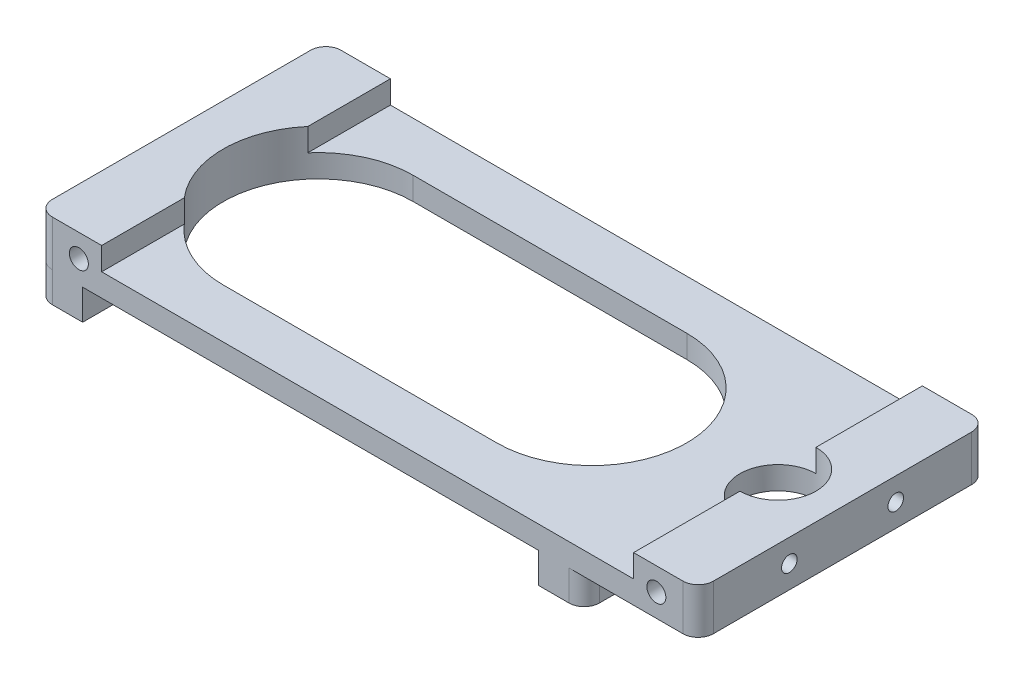
SolidWorks part; units mm, degrees
ref_plane "Front Plane" through (0, 0, 0) normal (0, 0, 1) x (1, 0, 0)
ref_plane "Top Plane" through (0, 0, 0) normal (0, 1, 0) x (1, 0, 0)
ref_plane "Right Plane" through (0, 0, 0) normal (1, 0, 0) x (0, 0, -1)
sketch "Sketch2" plane through (0, 0, 11.2) normal (0, 0, 1) x (1, 0, 0)
  line L1 (-84.0653, 85.9519) -> (-75.5653, 85.9519)
  line L2 (-84.0653, 85.9519) -> (-84.0653, 79.9519)
  line L3 (-84.0653, 79.9519) -> (2.9347, 79.9519)
  line L4 (2.9347, 85.9519) -> (2.9347, 79.9519)
  line L5 (-71.5653, 86.4519) -> (-82.0653, 86.4519) construction
  line L14 (-5.5653, 85.9519) -> (2.9347, 85.9519)
  line L16 (-75.5653, 85.9519) -> (-75.5653, 82.9519)
  line L17 (-75.5653, 82.9519) -> (-5.5653, 82.9519)
  line L18 (-5.5653, 85.9519) -> (-5.5653, 82.9519)
  circle A0 centre (-2.5653, 82.9519) radius 3 construction
  dimension "D1" = 0.5
  dimension "D2" = 5.5
  dimension "D3" = 5.5
  dimension "D4" = 6
  dimension "D5" = 3
  dimension "D6" = 8.5
extrude "Boss-Extrude1" add sketch "Sketch2" along normal blind 38
fillet "Fillet3" radius 2 4 edges at (-84.0653, 82.9519, 49.2) (-84.0653, 82.9519, 11.2) (2.9347, 82.9519, 11.2) (2.9347, 82.9519, 49.2)
sketch "Sketch3" plane through (0, 82.9519, 0) normal (0, 1, 0) x (1, 0, 0)
  line L0 (-84.0653, -47.2) -> (-84.0653, -13.2) construction
  line L1 (-5.5653, -11.2) -> (-75.5653, -11.2) construction
  line L2 (-66.0653, -42.7) -> (-30.0653, -42.7)
  line L3 (-66.0653, -17.7) -> (-30.0653, -17.7)
  arc A0 (-30.0653, -42.7) -> (-30.0653, -17.7) centre (-30.0653, -30.2) ccw
  arc A1 (-66.0653, -17.7) -> (-66.0653, -42.7) centre (-66.0653, -30.2) ccw
  dimension "D1" = 25
  dimension "D2" = 18
  dimension "D3" = 36
  dimension "D4" = 19
extrude "Cut-Extrude1" cut sketch "Sketch3" against normal through all and the other way through all
hole_wizard "M3x0.5 Tapped Hole3" positions "Sketch7" profile "Sketch6" tap size "M3x0.5" standard "Ansi Metric"
sketch "Sketch7" plane through (0, 0, 49.2) normal (0, 0, 1) x (1, 0, 0)
  line L0 (-75.5653, 82.9519) -> (-75.5653, 85.9519) construction
  line L1 (-82.0653, 79.9519) -> (0.9347, 79.9519) construction
  line L2 (-5.5653, 85.9519) -> (-5.5653, 82.9519) construction
  point P0 (-78.5653, 82.9519)
  point P1 (-2.5653, 82.9519)
  dimension "D1" = 3
  dimension "D2" = 3
  dimension "D3" = 3
  dimension "D4" = 3
sketch "Sketch6" plane through (-78.5653, 82.9519, 49.2) normal (1, 0, 0) x (0, -1, 0)
  line L0 (0, 0) -> (0, 8.2511)
  line L1 (0, 8.2511) -> (1.25, 7.5)
  line L2 (1.25, 7.5) -> (1.25, 0)
  line L5 (1.25, 0) -> (0, 0)
  line L10 (0, 8.2511) -> (-1.25, 7.5) construction
  line L11 (0, -6.35) -> (0, 107.95) construction
  dimension "Tap Drill Dia." = 2.5
  dimension "Tap Drill Depth" = 7.5
  dimension "Drill Angle" = 118
cosmetic thread "Hole Thread6" parameters "D1"=6, "D2"=3
cosmetic thread "Hole Thread7" parameters "D1"=6, "D2"=3
hole_wizard "M3x0.5 Tapped Hole4" positions "Sketch9" profile "Sketch8" tap size "M3x0.5" standard "Ansi Metric"
sketch "Sketch9" plane through (0, 0, 11.2) normal (0, 0, -1) x (-1, 0, 0)
  line L0 (75.5653, 82.9519) -> (75.5653, 85.9519) construction
  line L1 (82.0653, 79.9519) -> (-0.9347, 79.9519) construction
  line L2 (-0.9347, 85.9519) -> (5.5653, 85.9519) construction
  line L3 (5.5653, 85.9519) -> (5.5653, 82.9519) construction
  point P0 (2.5653, 82.9519)
  point P1 (78.5653, 82.9519)
  dimension "D1" = 3
  dimension "D2" = 3
  dimension "D3" = 3
  dimension "D4" = 3
sketch "Sketch8" plane through (-2.5653, 82.9519, 11.2) normal (1, 0, 0) x (0, 1, 0)
  line L0 (0, 0) -> (0, 8.2511)
  line L1 (0, 8.2511) -> (1.25, 7.5)
  line L2 (1.25, 7.5) -> (1.25, 0)
  line L5 (1.25, 0) -> (0, 0)
  line L10 (0, 8.2511) -> (-1.25, 7.5) construction
  line L11 (0, -6.35) -> (0, 107.95) construction
  dimension "Tap Drill Dia." = 2.5
  dimension "Tap Drill Depth" = 7.5
  dimension "Drill Angle" = 118
cosmetic thread "Hole Thread8" parameters "D1"=6, "D2"=3
cosmetic thread "Hole Thread9" parameters "D1"=6, "D2"=3
hole_wizard "M2.5x0.45 Tapped Hole1" positions "Sketch11" profile "Sketch10" tap size "M2.5x0.45" standard "Ansi Metric"
sketch "Sketch11" plane through (-84.0653, 0, 0) normal (-1, 0, 0) x (0, 0, 1)
  line L0 (11.2, 79.9519) -> (11.2, 85.9519) construction
  line L1 (47.2, 79.9519) -> (13.2, 79.9519) construction
  point P0 (23.2, 82.9519)
  point P1 (37.2, 82.9519)
  dimension "D1" = 12
  dimension "D2" = 3
  dimension "D3" = 3
  dimension "D4" = 12
sketch "Sketch10" plane through (-84.0653, 82.9519, 23.2) normal (0, 1, 0) x (0, 0, 1)
  line L0 (0, 0) -> (0, 6.9659)
  line L1 (0, 6.9659) -> (1.025, 6.35)
  line L2 (1.025, 6.35) -> (1.025, 0)
  line L5 (1.025, 0) -> (0, 0)
  line L10 (0, 6.9659) -> (-1.025, 6.35) construction
  line L11 (0, -6.35) -> (0, 107.95) construction
  dimension "Tap Drill Dia." = 2.05
  dimension "Tap Drill Depth" = 6.35
  dimension "Drill Angle" = 118
cosmetic thread "Hole Thread10" parameters "D1"=5, "D2"=2.5
cosmetic thread "Hole Thread11" parameters "D1"=5, "D2"=2.5
hole_wizard "M2.5x0.45 Tapped Hole2" positions "Sketch13" profile "Sketch12" tap size "M2.5x0.45" standard "Ansi Metric"
sketch "Sketch13" plane through (2.9347, 0, 0) normal (1, 0, 0) x (0, 0, -1)
  line L0 (-49.2, 79.9519) -> (-49.2, 85.9519) construction
  line L1 (-47.2, 79.9519) -> (-13.2, 79.9519) construction
  line L2 (-11.2, 85.9519) -> (-11.2, 79.9519) construction
  point P0 (-37.2, 82.9519)
  point P1 (-23.2, 82.9519)
  dimension "D1" = 12
  dimension "D2" = 3
  dimension "D3" = 3
  dimension "D4" = 12
sketch "Sketch12" plane through (2.9347, 82.9519, 37.2) normal (0, 1, 0) x (0, 0, -1)
  line L0 (0, 0) -> (0, 6.9659)
  line L1 (0, 6.9659) -> (1.025, 6.35)
  line L2 (1.025, 6.35) -> (1.025, 0)
  line L5 (1.025, 0) -> (0, 0)
  line L10 (0, 6.9659) -> (-1.025, 6.35) construction
  line L11 (0, -6.35) -> (0, 107.95) construction
  dimension "Tap Drill Dia." = 2.05
  dimension "Tap Drill Depth" = 6.35
  dimension "Drill Angle" = 118
cosmetic thread "Hole Thread12" parameters "D1"=5, "D2"=2.5
cosmetic thread "Hole Thread13" parameters "D1"=5, "D2"=2.5
sketch "Sketch14" plane through (0, 85.9519, 0) normal (0, 1, 0) x (1, 0, 0)
  line L0 (-5.5653, -49.2) -> (-5.5653, -11.2) construction
  circle A0 centre (-5.5653, -30.2) radius 5
  dimension "D1" = 10
extrude "Cut-Extrude2" cut sketch "Sketch14" against normal through all
sketch "Sketch16" plane through (0, 79.9519, 0) normal (0, -1, 0) x (1, 0, 0)
  line L0 (-82.0653, 49.2) -> (0.9347, 49.2) construction
  line L1 (-84.0653, 49.2) -> (-78.0653, 49.2)
  line L2 (-84.0653, 49.2) -> (-84.0653, 43.2)
  line L3 (-84.0653, 43.2) -> (-78.0653, 43.2)
  line L4 (-78.0653, 49.2) -> (-78.0653, 43.2)
  line L5 (-84.0653, 11.2) -> (-78.0653, 11.2)
  line L6 (-84.0653, 11.2) -> (-84.0653, 17.2)
  line L7 (-84.0653, 17.2) -> (-78.0653, 17.2)
  line L8 (-78.0653, 11.2) -> (-78.0653, 17.2)
  line L9 (-12.0653, 49.2) -> (-18.0653, 49.2)
  line L10 (-12.0653, 49.2) -> (-12.0653, 43.2)
  line L11 (-12.0653, 43.2) -> (-18.0653, 43.2)
  line L12 (-18.0653, 49.2) -> (-18.0653, 43.2)
  line L13 (-82.0653, 11.2) -> (0.9347, 11.2) construction
  line L14 (-12.0653, 11.2) -> (-18.0653, 11.2)
  line L15 (-12.0653, 11.2) -> (-12.0653, 17.2)
  line L16 (-12.0653, 17.2) -> (-18.0653, 17.2)
  line L17 (-18.0653, 11.2) -> (-18.0653, 17.2)
  line L18 (-84.0653, 47.2) -> (-84.0653, 13.2) construction
  dimension "D1" = 6
  dimension "D2" = 6
  dimension "D3" = 6
  dimension "D4" = 6
  dimension "D5" = 6
  dimension "D6" = 6
  dimension "D7" = 6
  dimension "D8" = 6
  dimension "D9" = 60
  dimension "D10" = 60
extrude "Boss-Extrude2" add sketch "Sketch16" along normal blind 4
fillet "Fillet4" radius 2 8 edges at (-12.0653, 77.9519, 49.2) (-12.0653, 77.9519, 11.2) (-84.0653, 77.9519, 11.2) (-84.0653, 77.9519, 49.2) (-78.0653, 77.9519, 43.2) (-78.0653, 77.9519, 17.2) (-18.0653, 77.9519, 17.2) (-18.0653, 77.9519, 43.2)
hole_wizard "M3x0.5 Tapped Hole5" positions "Sketch18" profile "Sketch17" tap size "M3x0.5" standard "Ansi Metric"
sketch "Sketch18" plane through (0, 75.9519, 0) normal (0, -1, 0) x (1, 0, 0)
  line L0 (-16.0653, 43.2) -> (-12.0653, 43.2) construction
  line L1 (-18.0653, 49.2) -> (-18.0653, 45.2) construction
  line L2 (-12.0653, 17.2) -> (-16.0653, 17.2) construction
  line L3 (-18.0653, 15.2) -> (-18.0653, 11.2) construction
  line L5 (-80.0653, 17.2) -> (-84.0653, 17.2) construction
  line L6 (-78.0653, 11.2) -> (-78.0653, 15.2) construction
  line L7 (-84.0653, 43.2) -> (-80.0653, 43.2) construction
  line L8 (-78.0653, 45.2) -> (-78.0653, 49.2) construction
  point P0 (-81.0653, 46.2)
  point P1 (-81.0653, 14.2)
  point P3 (-15.0653, 14.2)
  point P5 (-15.0653, 46.2)
  dimension "D1" = 3
  dimension "D2" = 3
  dimension "D3" = 3
  dimension "D4" = 3
  dimension "D5" = 3
  dimension "D6" = 3
  dimension "D7" = 3
  dimension "D8" = 3
sketch "Sketch17" plane through (-81.0653, 75.9519, 46.2) normal (1, 0, 0) x (0, 0, -1)
  line L0 (0, 0) -> (0, 6.2511)
  line L1 (0, 6.2511) -> (1.25, 5.5)
  line L2 (1.25, 5.5) -> (1.25, 0)
  line L5 (1.25, 0) -> (0, 0)
  line L10 (0, 6.2511) -> (-1.25, 5.5) construction
  line L11 (0, -6.35) -> (0, 107.95) construction
  dimension "Tap Drill Dia." = 2.5
  dimension "Tap Drill Depth" = 5.5
  dimension "Drill Angle" = 118
cosmetic thread "Hole Thread14" parameters "D1"=5, "D2"=3
cosmetic thread "Hole Thread15" parameters "D1"=5, "D2"=3
cosmetic thread "Hole Thread16" parameters "D1"=5, "D2"=3
cosmetic thread "Hole Thread17" parameters "D1"=5, "D2"=3
